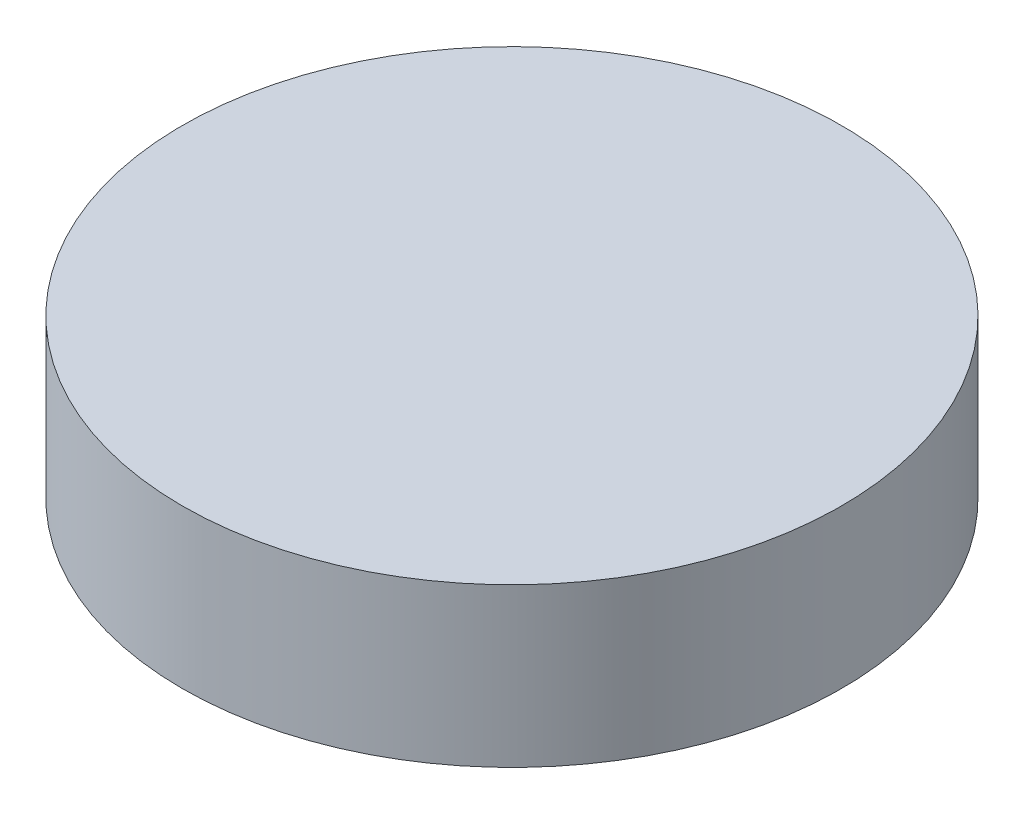
SolidWorks part; units mm, degrees
ref_plane "Front Plane" through (0, 0, 0) normal (0, 0, 1) x (1, 0, 0)
ref_plane "Top Plane" through (0, 0, 0) normal (0, 1, 0) x (1, 0, 0)
ref_plane "Right Plane" through (0, 0, 0) normal (1, 0, 0) x (0, 0, -1)
other "Configuration Table"
sketch "Sketch1" plane through (0, 0, 0) normal (0, 1, 0) x (1, 0, 0)
  circle A0 centre (50, 770) radius 25
extrude "PACK_ayar_ayagi_3" add sketch "Sketch1" along normal blind 12 separate body
